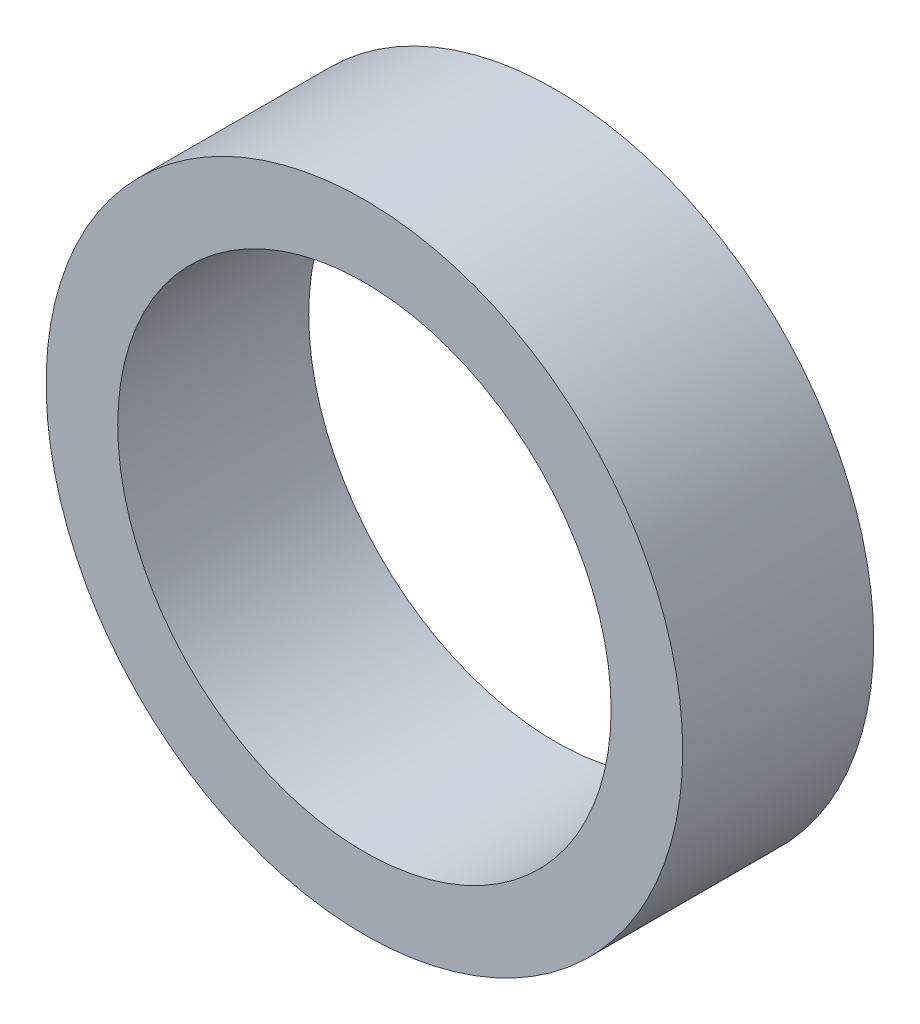
SolidWorks part; units mm, degrees
material "Alloy Steel"
ref_plane "Front Plane" through (0, 0, 0) normal (0, 0, 1) x (1, 0, 0)
ref_plane "Top Plane" through (0, 0, 0) normal (0, 1, 0) x (1, 0, 0)
ref_plane "Right Plane" through (0, 0, 0) normal (1, 0, 0) x (0, 0, -1)
sketch "Sketch1" plane through (0, 0, 0) normal (0, 0, 1) x (1, 0, 0)
  circle A0 centre (0, 0) radius 10
  circle A1 centre (0, 0) radius 7.75
  dimension "D1" = 20
  dimension "D2" = 15.5
extrude "Boss-Extrude1" add sketch "Sketch1" along normal blind 6
